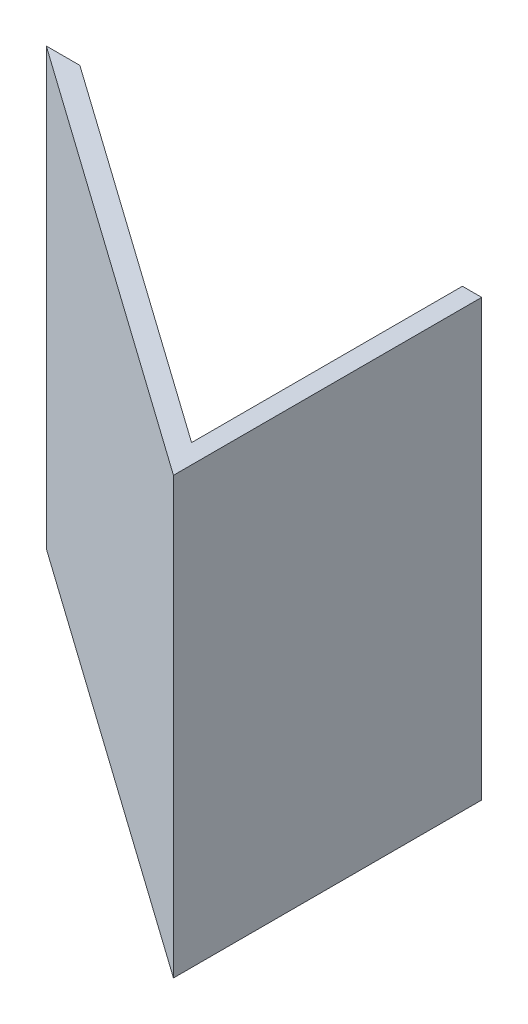
SolidWorks part; units mm, degrees
ref_plane "Front Plane" through (0, 0, 0) normal (0, 0, 1) x (1, 0, 0)
ref_plane "Top Plane" through (0, 0, 0) normal (0, 1, 0) x (1, 0, 0)
ref_plane "Right Plane" through (0, 0, 0) normal (1, 0, 0) x (0, 0, -1)
sketch "Sketch1" plane through (0, 0, 0) normal (0, 1, 0) x (1, 0, 0)
  line L1 (65.0271, 34.1908) -> (65.0271, -16.6092)
  line L2 (-6.7279, 34.1908) -> (65.0271, -16.6092)
  line L3 (-6.7279, 34.1908) -> (-1.2008, 34.1908)
  line L4 (65.0271, 34.1908) -> (61.8521, 34.1908)
  line L5 (61.8521, 34.1908) -> (61.8521, -10.4497)
  line L15 (-1.2008, 34.1908) -> (61.8521, -10.4497)
  point P4 (-3.9644, 34.1908)
  point P7 (0, 0)
extrude "Boss-Extrude1" add sketch "Sketch1" along normal blind 71.755
